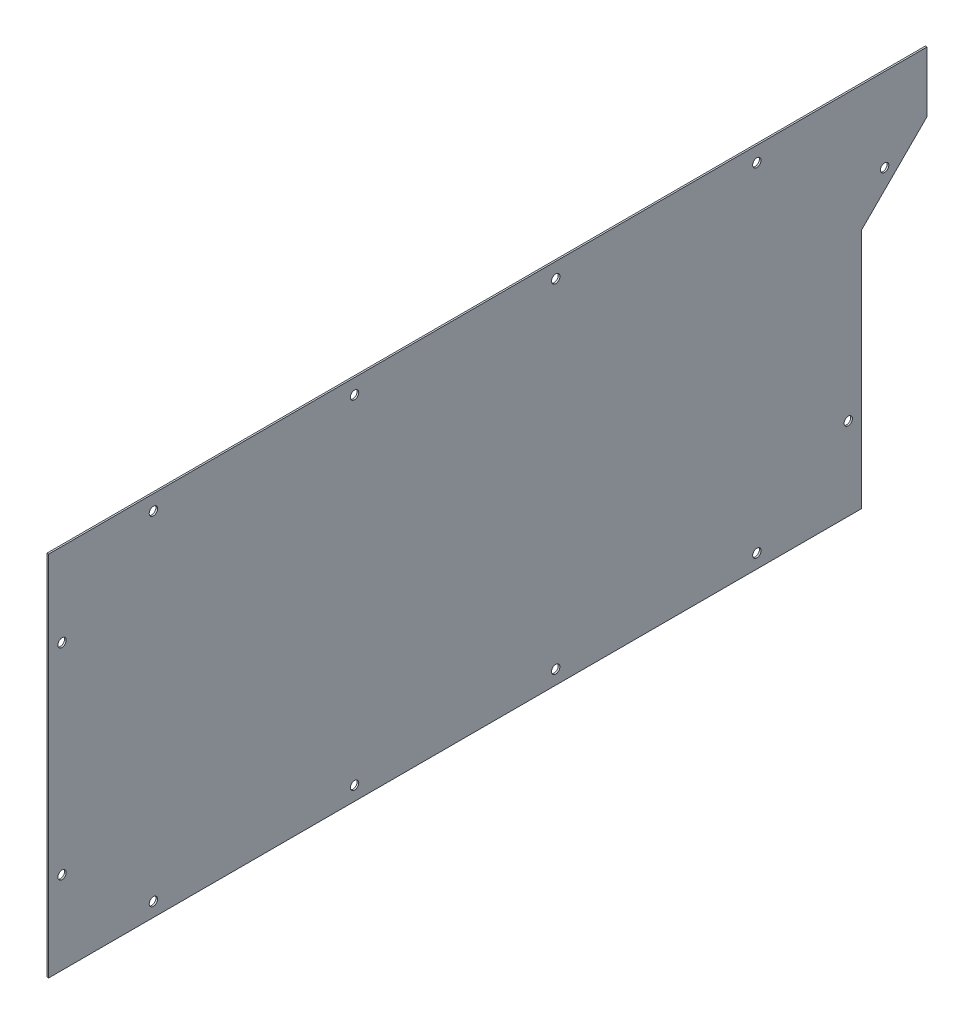
SolidWorks part; units mm, degrees
ref_plane "Front" through (0, 0, 0) normal (0, 0, 1) x (1, 0, 0)
ref_plane "Top" through (0, 0, 0) normal (0, 1, 0) x (1, 0, 0)
ref_plane "Right" through (0, 0, 0) normal (1, 0, 0) x (0, 0, -1)
sketch "Эскиз1" plane through (0, 0, 0) normal (1, 0, 0) x (0, 0, -1)
  line L0 (223, -109.5) -> (223, 34.5)
  line L1 (-262, -109.5) -> (223, -109.5)
  line L2 (-262, -109.5) -> (-262, 109.5)
  line L3 (-262, 109.5) -> (262, 109.5)
  line L4 (262, 73.5) -> (262, 109.5)
  line L5 (-262, -109.5) -> (262, 109.5) construction
  line L6 (-262, 109.5) -> (262, -109.5) construction
  line L7 (223, 34.5) -> (262, 73.5)
  line L8 (223, -109.5) -> (262, -109.5) construction
  line L9 (262, -109.5) -> (262, 73.5) construction
  point P0 (0, 0)
  point P8 (262, 91.5)
  dimension "D1" = 524
  dimension "D2" = 219
  dimension "D3" = 39
  dimension "D4" = 135
  dimension "D5" = 144
extrude "Бобышка-Вытянуть1" add sketch "Эскиз1" along normal blind 1
sketch "Эскиз2" plane through (1, 0, 0) normal (1, 0, 0) x (0, 0, -1)
  line L0 (-199.5, -101.2071) -> (160.5, -101.2071) construction
  line L1 (-199.5, -98.7071) -> (160.5, -98.7071) construction
  line L2 (160.5, 100.5) -> (-199.5, 100.5) construction
  line L3 (-254, -60.2071) -> (-254, 59.7929) construction
  line L4 (-254, -60.2071) -> (-199.5, -101.2071) construction
  line L5 (-197.9971, -99.2093) -> (-252.4971, -58.2093) construction
  line L6 (-251.5, -60.2071) -> (-251.5, 59.7929) construction
  line L7 (-199.5, 103) -> (160.5, 103) construction
  line L8 (-202, 100.5) -> (-202, -101.2071) construction
  line L9 (-254, 62.2929) -> (236.6863, 62.2929) construction
  line L10 (-254, -62.7071) -> (215, -62.7071) construction
  circle A0 centre (40.5, -101.2071) radius 2.5
  circle A1 centre (160.5, -101.2071) radius 2.5
  circle A2 centre (-79.5, -101.2071) radius 2.5
  circle A3 centre (-199.5, -101.2071) radius 2.5
  circle A4 centre (215, -60.2071) radius 2.5
  circle A5 centre (236.6863, 59.7929) radius 2.5
  circle A6 centre (-254, 59.7929) radius 2.5
  circle A7 centre (-254, -60.2071) radius 2.5
  circle A8 centre (-199.5, 100.5) radius 2.5
  circle A9 centre (-79.5, 100.5) radius 2.5
  circle A10 centre (40.5, 100.5) radius 2.5
  circle A11 centre (160.5, 100.5) radius 2.5
  dimension "D1" = 5
extrude "Вырез-Вытянуть1" cut sketch "Эскиз2" against normal up to next
